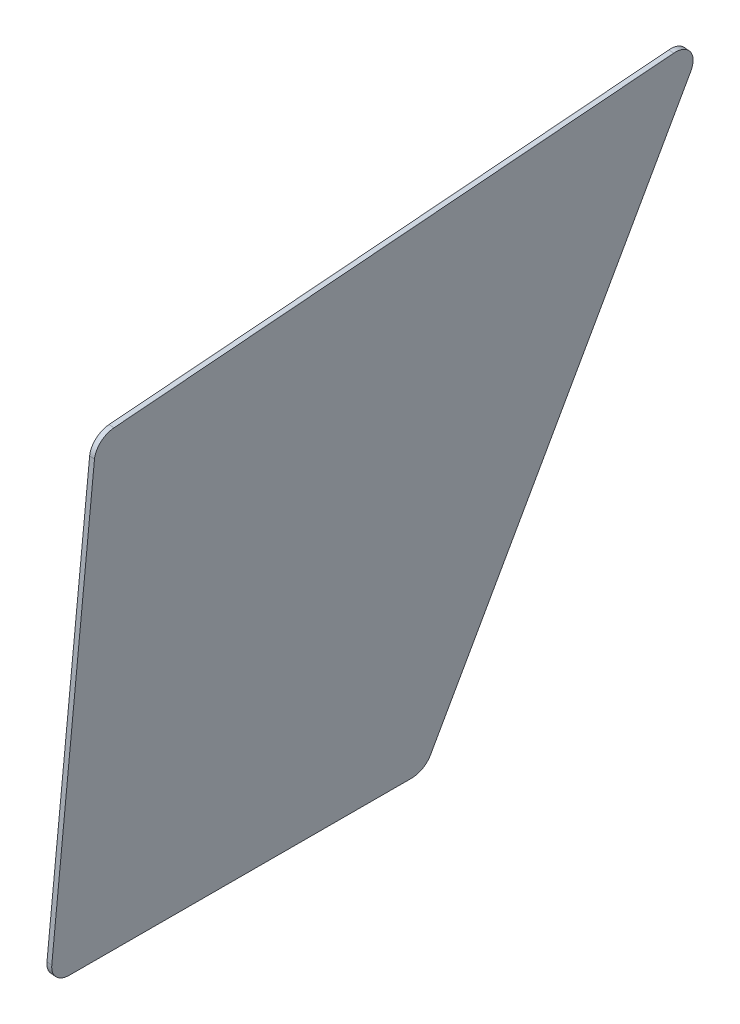
SolidWorks part; units mm, degrees
material "Acrylic (Medium-high impact)"
ref_plane "Front Plane" through (0, 0, 0) normal (0, 0, 1) x (1, 0, 0)
ref_plane "Top Plane" through (0, 0, 0) normal (0, 1, 0) x (1, 0, 0)
ref_plane "Right Plane" through (0, 0, 0) normal (1, 0, 0) x (0, 0, -1)
sketch "Sketch2" plane through (125.925, -11.7005, 0) normal (0.9957, -0.0925, 0) x (0, 0, -1)
  line L0 (-1098.9637, 120.8587) -> (-1344.0413, 121.2656) construction
  line L1 (-948.2115, 482.775) -> (-1098.9637, 120.8587) construction
  line L2 (-1344.0413, 447.5747) -> (-948.2115, 482.775) construction
  line L3 (-1344.0413, 121.2656) -> (-1344.0413, 447.5747) construction
  line L4 (-1098.9637, 120.8587) -> (-1344.0413, 121.2656)
  line L5 (-948.2115, 482.775) -> (-1098.9637, 120.8587)
  line L6 (-1344.0413, 447.5747) -> (-948.2115, 482.775)
  line L7 (-1344.0413, 121.2656) -> (-1344.0413, 447.5747)
extrude "Boss-Extrude2" add sketch "Sketch2" along normal up to vertex (3.175 mm away) from vertex at 0
fillet "Fillet1" radius 12.7 4 edges at (138.6873, 108.4929, 1098.9637) (138.725, 108.8981, 1344.0413) (172.1712, 468.8569, 948.2115) (168.9145, 433.8076, 1344.0413)
